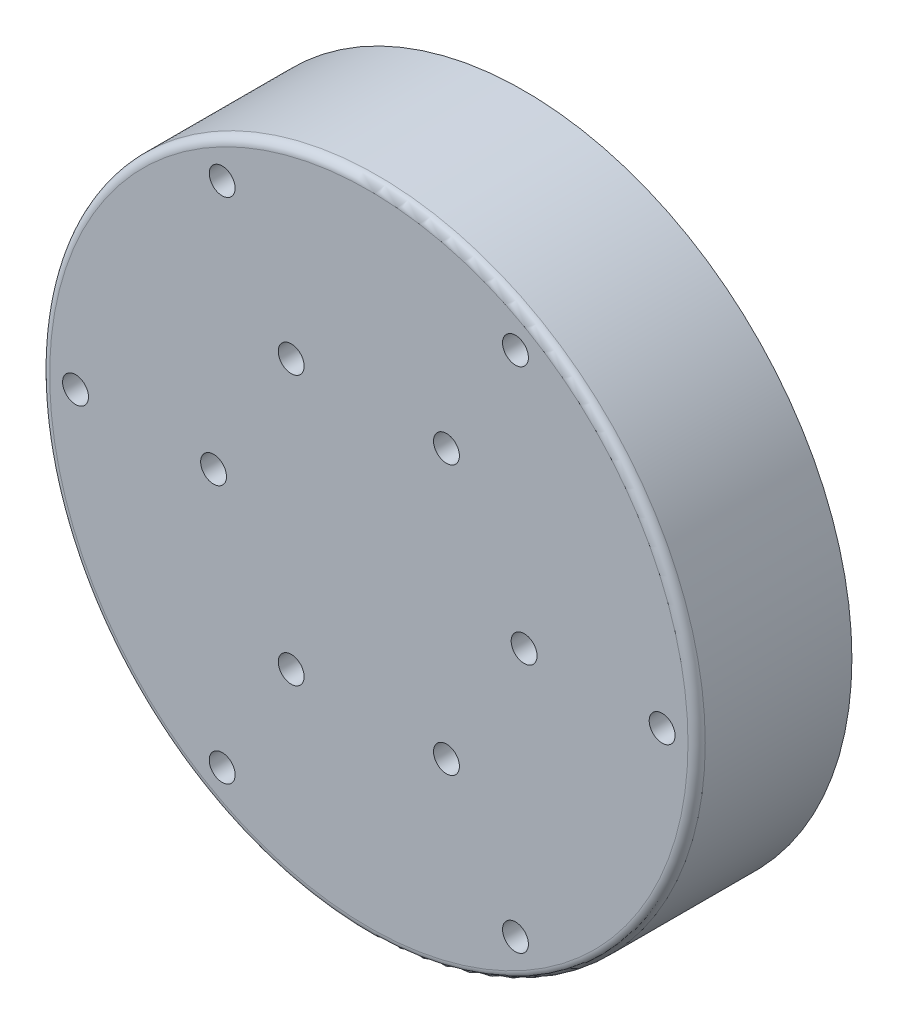
SolidWorks part; units mm, degrees
material "ABS"
ref_plane "Спереди" through (0, 0, 0) normal (0, 0, 1) x (1, 0, 0)
ref_plane "Сверху" through (0, 0, 0) normal (0, 1, 0) x (1, 0, 0)
ref_plane "Справа" through (0, 0, 0) normal (1, 0, 0) x (0, 0, -1)
other "Configuration Table"
sketch "Эскиз1" plane through (0, 0, 0) normal (0, 0, 1) x (1, 0, 0)
  circle A0 centre (0, 0) radius 38
  dimension "D1" = 76
extrude "Бобышка-Вытянуть1" add sketch "Эскиз1" along normal blind 18
sketch "Эскиз2" plane through (0, 0, 18) normal (0, 0, 1) x (1, 0, 0)
  line L0 (0, 0) -> (-34, 0) construction
  line L1 (0, 0) -> (-17, 29.4449) construction
  circle A0 centre (0, 0) radius 34 construction
  circle A1 centre (-34, 0) radius 1.5
  circle A2 centre (0, 0) radius 34 construction
  circle A3 centre (-17, 29.4449) radius 1.5
  circle A4 centre (0, 0) radius 34 construction
  circle A5 centre (17, 29.4449) radius 1.5
  circle A6 centre (0, 0) radius 34 construction
  circle A7 centre (34, 0) radius 1.5
  circle A8 centre (0, 0) radius 34 construction
  circle A9 centre (17, -29.4449) radius 1.5
  circle A10 centre (0, 0) radius 34 construction
  circle A11 centre (-17, -29.4449) radius 1.5
  dimension "D1" = 68
  dimension "D2" = 3
  dimension "D4" = 60
  dimension "D3" = 6
extrude "Вырез-Вытянуть1" cut sketch "Эскиз2" against normal up to next contours A7 | A5 | A3 | A1 | A11 | A9
sketch "Эскиз3" plane through (0, 0, 0) normal (0, 0, -1) x (-1, 0, 0)
  line L0 (-13.0767, -27) -> (13.0767, -27)
  arc A0 (13.0767, -27) -> (-13.0767, -27) centre (0, 0) ccw
  dimension "D1" = 60
  dimension "D2" = 27
extrude "Вырез-Вытянуть2" cut sketch "Эскиз3" against normal blind 12.5
fillet "Скругление1" radius 1 1 edges at (38, 0, 18)
ref_plane "Плоскость1" through (0, -27, 0) normal (0, 1, 0) x (1, 0, 0)
sketch "Эскиз6" plane through (0, -27, 0) normal (0, 1, 0) x (1, 0, 0)
  line L0 (38, 0) -> (-38, 0) construction
  line L1 (-10, -8.5) -> (10, -8.5)
  line L2 (-10, -8.5) -> (-10, -12.5)
  line L3 (-10, -12.5) -> (10, -12.5)
  line L4 (10, -8.5) -> (10, -12.5)
  line L5 (-10, -8.5) -> (10, -12.5) construction
  line L6 (-10, -12.5) -> (10, -8.5) construction
  line L7 (0, 24) -> (0, -24) construction
  point P0 (0, -10.5)
  point P11 (0, 0)
  dimension "D1" = 4
  dimension "D2" = 20
  dimension "D3" = 8.5
  dimension "D4" = 10
extrude "Вырез-Вытянуть7" cut sketch "Эскиз6" against normal up to next
sketch "Эскиз7" plane through (0, 0, 18) normal (0, 0, 1) x (1, 0, 0)
  line L0 (0, 0) -> (-18, 0) construction
  circle A1 centre (0, 0) radius 18 construction
  circle A2 centre (-18, 0) radius 1.5
  circle A4 centre (-9, 15.5885) radius 1.5
  circle A6 centre (9, 15.5885) radius 1.5
  circle A8 centre (18, 0) radius 1.5
  circle A10 centre (9, -15.5885) radius 1.5
  circle A12 centre (-9, -15.5885) radius 1.5
  circle A13 centre (0, 0) radius 18 [skipped]
  circle A14 centre (0, 0) radius 18 [skipped]
  circle A15 centre (0, 0) radius 18 [skipped]
  circle A16 centre (0, 0) radius 18 [skipped]
  circle A17 centre (0, 0) radius 18 [skipped]
  dimension "D3" = 6
  dimension "D1" = 36
  dimension "D2" = 3
extrude "Вырез-Вытянуть8" cut sketch "Эскиз7" against normal up to next
ref_point "Точка1"
